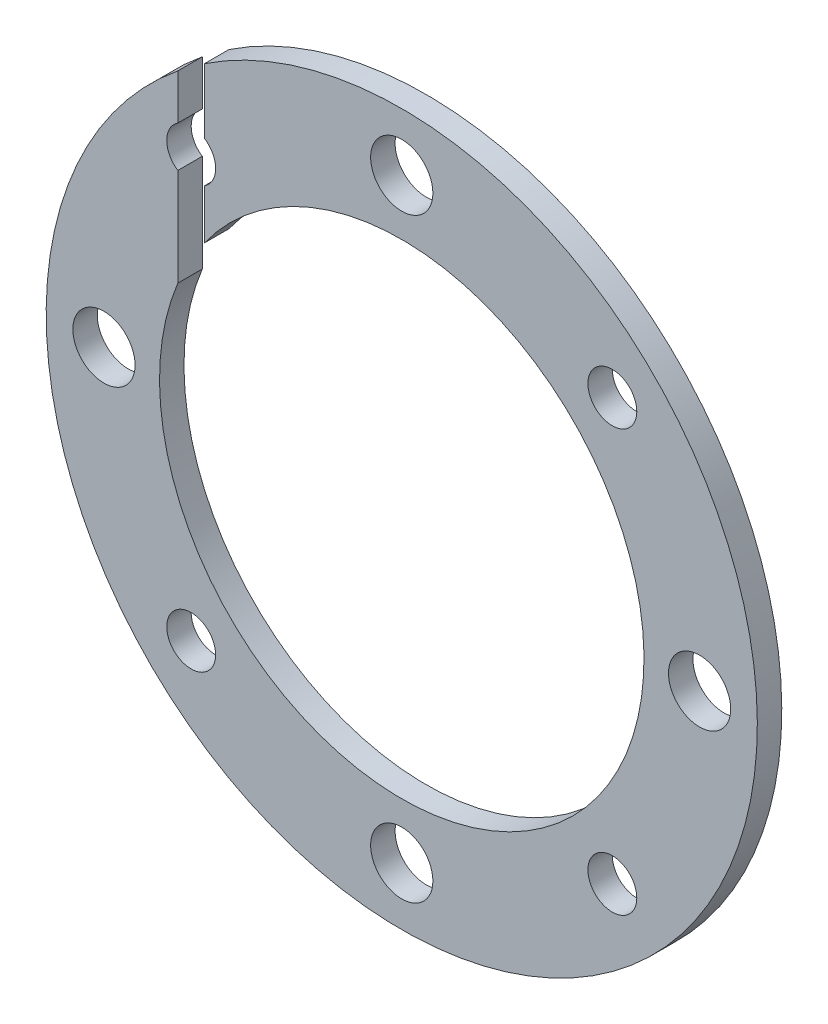
SolidWorks part; units mm, degrees
material "PLA"
ref_plane "Front Plane" through (0, 0, 0) normal (0, 0, 1) x (1, 0, 0)
ref_plane "Top Plane" through (0, 0, 0) normal (0, 1, 0) x (1, 0, 0)
ref_plane "Right Plane" through (0, 0, 0) normal (1, 0, 0) x (0, 0, -1)
sketch "Sketch1" plane through (0, 0, 0) normal (0, 0, 1) x (1, 0, 0)
  line L0 (0, -1000) -> (0, 49000) construction
  line L1 (-707.1068, -707.1068) -> (34648.2323, 34648.2323) construction
  circle A0 centre (0, 0) radius 40.64
  circle A1 centre (0, 0) radius 27.686
  circle A2 centre (0, 34.036) radius 3.556
  circle A3 centre (0, 0) radius 34.036
  circle A4 centre (34.036, 0) radius 3.556
  circle A5 centre (0, -34.036) radius 3.556
  circle A6 centre (-34.036, 0) radius 3.556
  circle A7 centre (24.0671, 24.0671) radius 2.794
  circle A8 centre (24.0671, -24.0671) radius 2.794
  circle A9 centre (-24.0671, -24.0671) radius 2.794
  circle A10 centre (-24.0671, 24.0671) radius 2.794
  point P18 (0, 0)
  point P29 (0, 0)
  dimension "D1" = 81.28
  dimension "D2" = 55.372
  dimension "D3" = 68.072
  dimension "D4" = 7.112
  dimension "D6" = 5.588
  dimension "D5" = 4
  dimension "D7" = 4
extrude "Boss-Extrude1" add sketch "Sketch1" along normal blind 2.794 contours A0 A10 A3 A2 A7 A4 A8 A5 A9 A6 | A10 A3 A6 A9 A5 A8 A4 A7 A2 A1
sketch "Sketch2" plane through (0, 0, 2.794) normal (0, 0, 1) x (1, 0, 0)
  line L5 (-22.5431, 48.1342) -> (-25.5911, 48.1342)
  line L6 (-22.5431, 48.1342) -> (-22.5431, 0)
  line L7 (-22.5431, 0) -> (-25.5911, 0)
  line L8 (-25.5911, 48.1342) -> (-25.5911, 0)
  line L9 (-22.5431, 48.1342) -> (-25.5911, 0) construction
  line L10 (-22.5431, 0) -> (-25.5911, 48.1342) construction
  circle A3 centre (-24.0671, 24.0671) radius 2.794 construction
  dimension "D1" = 3.048
extrude "Cut-Extrude1" cut sketch "Sketch2" against normal blind 14.097
